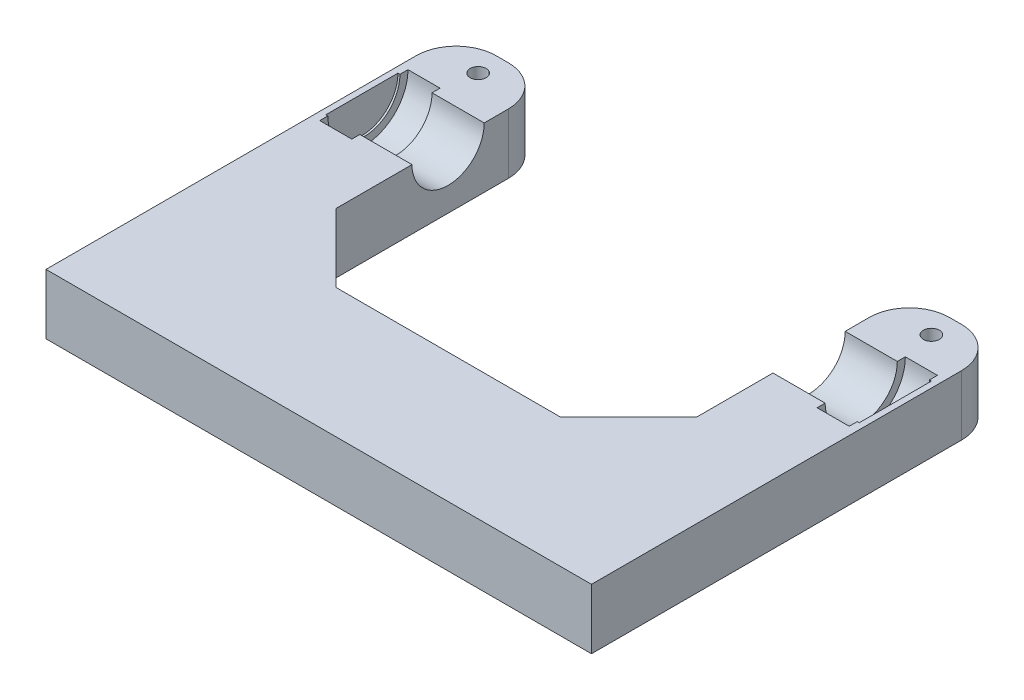
SolidWorks part; units mm, degrees
ref_plane "Front Plane" through (0, 0, 0) normal (0, 0, 1) x (1, 0, 0)
ref_plane "Top Plane" through (0, 0, 0) normal (0, 1, 0) x (1, 0, 0)
ref_plane "Right Plane" through (0, 0, 0) normal (1, 0, 0) x (0, 0, -1)
sketch "Sketch1" plane through (0, 0, 0) normal (0, 1, 0) x (1, 0, 0)
  line L0 (-45, 25) -> (-68, 25)
  line L1 (-41, 41) -> (41, 41) construction
  line L2 (-41, 41) -> (-41, -41) construction
  line L3 (-41, -41) -> (41, -41) construction
  line L4 (41, 41) -> (41, -41) construction
  line L5 (-41, 41) -> (41, -41) construction
  line L6 (-41, -41) -> (41, 41) construction
  line L7 (-45, 45) -> (45, 45) construction
  line L8 (-45, 45) -> (-45, -45) construction
  line L9 (-45, -45) -> (45, -45)
  line L10 (45, 45) -> (45, -45) construction
  line L11 (-45, 45) -> (45, -45) construction
  line L12 (-45, -45) -> (45, 45) construction
  line L13 (-68, 25) -> (-68, -77.2494)
  line L14 (-68, -77.2494) -> (68, -77.2494)
  line L15 (0, -55) -> (0, 55) construction
  line L16 (68, 25) -> (68, -77.2494)
  line L17 (45, 25) -> (68, 25)
  line L18 (-45, -45) -> (-45, 25)
  line L19 (45, 25) -> (45, -45)
  point P0 (0, 0)
  point P5 (0, 0)
  point P18 (0, -77.2494)
  point P20 (0, 0)
  dimension "D1" = 82
  dimension "D2" = 90
  dimension "D3" = 23
  dimension "D4" = 25
extrude "Boss-Extrude1" add sketch "Sketch1" against normal blind 15
sketch "Sketch2" plane through (0, 0, 0) normal (1, 0, 0) x (0, 0, -1)
  circle A0 centre (0, 0) radius 9
  dimension "D1" = 18
extrude "Cut-Extrude1" cut sketch "Sketch2" against normal blind 66.5
sketch "Sketch4" plane through (0, 0, 0) normal (1, 0, 0) x (0, 0, -1)
  circle A0 centre (0, 0) radius 11
  dimension "D1" = 22
extrude "Cut-Extrude2" cut sketch "Sketch4" against normal blind 8 from offset 58 offset against normal yes
chamfer "Chamfer1" distance 17 angle 45 2 edges at (45, -7.5, 45) (-45, -7.5, 45)
sketch "Sketch5" plane through (0, 0, 0) normal (0, 1, 0) x (1, 0, 0)
  line L0 (-56.5, 25) -> (-56.5, 19) construction
  line L1 (-45, 25) -> (-68, 25) construction
  circle A0 centre (-56.5, 19) radius 2
  dimension "D2" = 4
  dimension "D1" = 6
extrude "Cut-Extrude3" cut sketch "Sketch5" against normal through all
fillet "Fillet1" radius 10 4 edges at (-45, -7.5, -25) (-68, -7.5, -25) (68, -7.5, -25) (45, -7.5, -25)
mirror "Mirror2" about plane through (0, 0, 0) normal (1, 0, 0) of "Cut-Extrude1", "Cut-Extrude2", "Cut-Extrude3"
